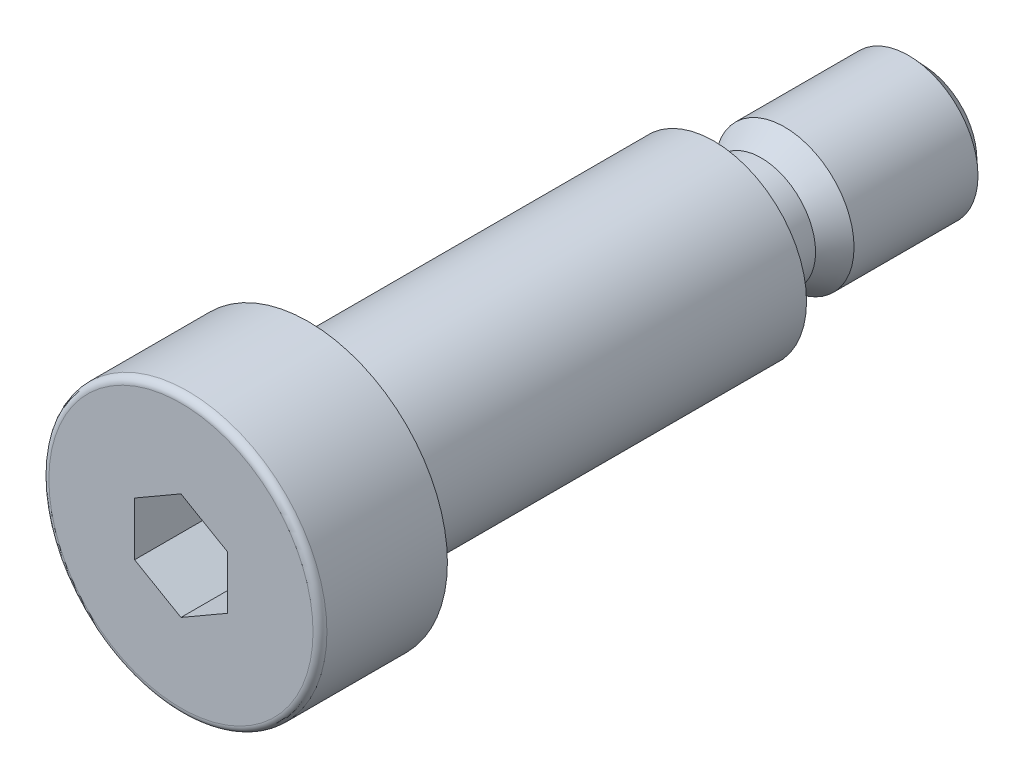
SolidWorks part; units mm, degrees
material "1.0545 (S355N)"
ref_plane "Płaszczyzna przednia" through (0, 0, 0) normal (0, 0, 1) x (1, 0, 0)
ref_plane "Płaszczyzna górna" through (0, 0, 0) normal (0, 1, 0) x (1, 0, 0)
ref_plane "Płaszczyzna prawa" through (0, 0, 0) normal (1, 0, 0) x (0, 0, -1)
sketch "Szkic1" plane through (0, 0, 0) normal (0, 1, 0) x (1, 0, 0)
  line L0 (6, 23.6) -> (4.7, 21.58)
  line L1 (12, -28.5) -> (-12, -28.5)
  line L2 (12, -28.5) -> (12, -17.5)
  line L3 (12, -17.5) -> (-12, -17.5)
  line L4 (-12, -28.5) -> (-12, -17.5)
  line L5 (8, -17.5) -> (-8, -17.5)
  line L6 (8, -17.5) -> (8, 17.5)
  line L7 (8, 17.5) -> (-8, 17.5)
  line L8 (-8, -17.5) -> (-8, 17.5)
  line L9 (-4.7, 17.5) -> (4.7, 17.5)
  line L10 (-4.7, 17.5) -> (-4.7, 21.58)
  line L11 (-4.7, 21.58) -> (4.7, 21.58)
  line L12 (4.7, 17.5) -> (4.7, 21.58)
  line L13 (6, 23.6) -> (6, 34.3)
  line L14 (6, 34.3) -> (4.7, 35.5)
  line L15 (4.7, 35.5) -> (-4.7, 35.5)
  line L16 (-4.7, 35.5) -> (-6, 34.3)
  line L17 (-6, 34.3) -> (-6, 23.6)
  line L18 (-6, 23.6) -> (-4.7, 21.58)
  line L19 (6, 23.6) -> (-6, 23.6) construction
  line L20 (6, 34.3) -> (-6, 34.3) construction
  line L21 (0, -19.9356) -> (0, 25.6583) construction
  line L22 (0, -28.5) -> (0, 35.5)
  point P4 (0, -17.5)
  point P14 (0, -17.5)
  point P15 (0, 17.5)
  point P16 (0, 17.5)
  point P17 (-8, 0)
  point P23 (0, 23.6)
  point P25 (0, 35.5)
  point P26 (0, 21.58)
  point P27 (0, 34.3)
  dimension "D1" = 24
  dimension "D2" = 11
  dimension "D3" = 16
  dimension "l1" = 35
  dimension "D5" = 9.4
  dimension "D6" = 18
  dimension "D7" = 12
  dimension "D8" = 9.4
  dimension "D9" = 1.2
  dimension "D10" = 2.02
  dimension "D11" = 10.7
revolve "Obrót1" add sketch "Szkic1" angle 360 about L22
sketch "Szkic2" plane through (0, 0, 28.5) normal (0, 0, 1) x (1, 0, 0)
  line L1 (4, 2.3094) -> (0, 4.6188)
  line L2 (0, 4.6188) -> (-4, 2.3094)
  line L3 (-4, 2.3094) -> (-4, -2.3094)
  line L4 (-4, -2.3094) -> (0, -4.6188)
  line L5 (0, -4.6188) -> (4, -2.3094)
  line L6 (4, -2.3094) -> (4, 2.3094)
  circle A0 centre (0, 0) radius 4 construction
  dimension "D1" = 8
extrude "Wytnij-wyciągnięcie1" cut sketch "Szkic2" against normal blind 6.6
fillet "Zaokrąglenie1" radius 0.6 1 edges at (12, 0, 28.5)
